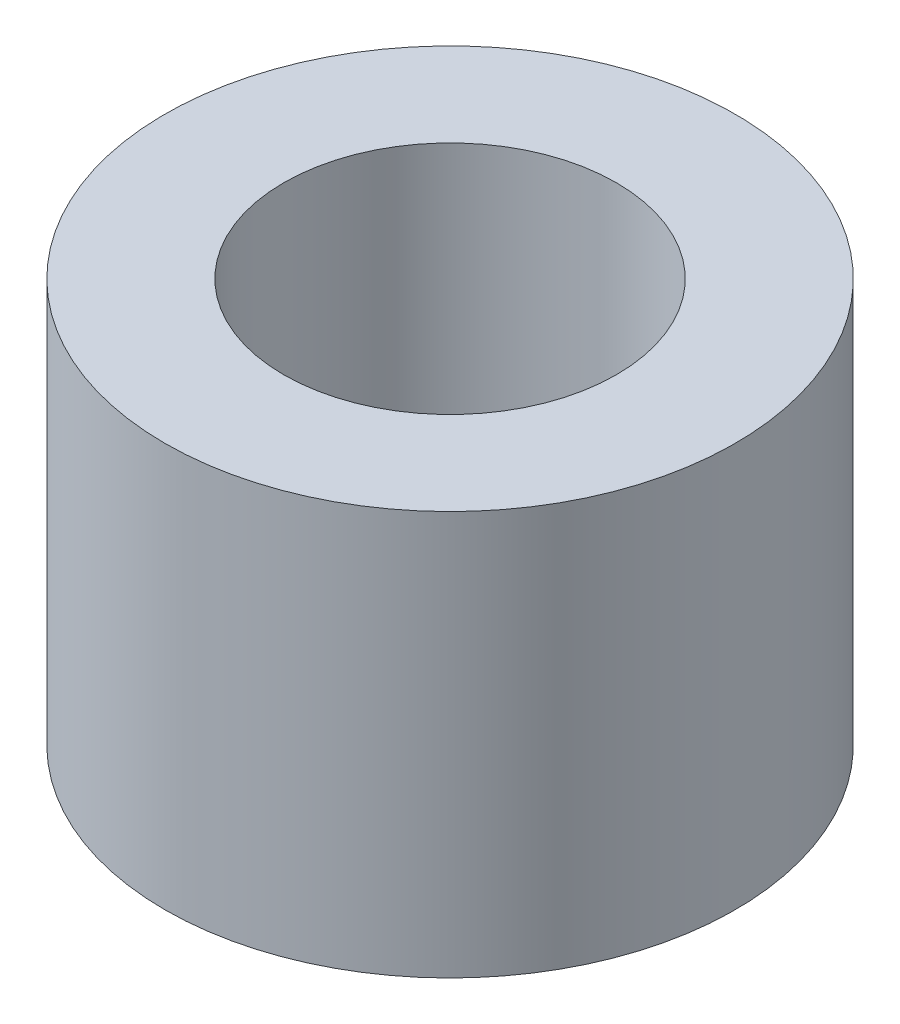
SolidWorks part; units mm, degrees
ref_plane "Front Plane" through (0, 0, 0) normal (0, 0, 1) x (1, 0, 0)
ref_plane "Top Plane" through (0, 0, 0) normal (0, 1, 0) x (1, 0, 0)
ref_plane "Right Plane" through (0, 0, 0) normal (1, 0, 0) x (0, 0, -1)
sketch "Sketch1" plane through (0, 0, 0) normal (0, 1, 0) x (1, 0, 0)
  circle A0 centre (0, 0) radius 3.5
  circle A1 centre (0, 0) radius 6
  dimension "D1" = 7
  dimension "D2" = 2.5
extrude "Boss-Extrude1" add sketch "Sketch1" along normal blind 8.5
